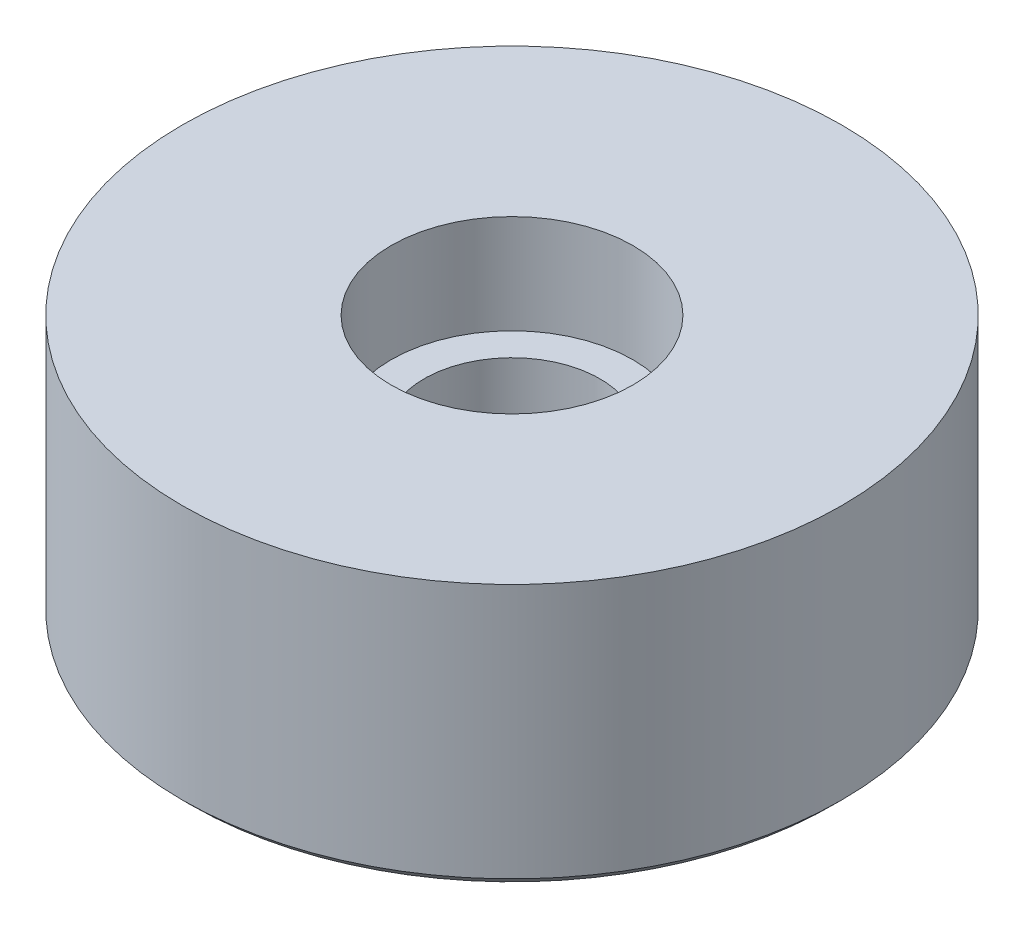
SolidWorks part; units mm, degrees
ref_plane "Front Plane" through (0, 0, 0) normal (0, 0, 1) x (1, 0, 0)
ref_plane "Top Plane" through (0, 0, 0) normal (0, 1, 0) x (1, 0, 0)
ref_plane "Right Plane" through (0, 0, 0) normal (1, 0, 0) x (0, 0, -1)
sketch "Sketch1" plane through (0, 0, 0) normal (0, 1, 0) x (1, 0, 0)
  circle A0 centre (0, 0) radius 15
  circle A1 centre (0, 0) radius 4
  dimension "D1" = 30
  dimension "D2" = 8
extrude "Boss-Extrude1" add sketch "Sketch1" along normal blind 12
ref_plane "Plane1" through (0, 12, 0) normal (0, 1, 0) x (1, 0, 0)
sketch "Sketch2" plane through (0, 12, 0) normal (0, 1, 0) x (1, 0, 0)
  circle A0 centre (0, 0) radius 5.5
  dimension "D1" = 11
extrude "Cut-Extrude1" cut sketch "Sketch2" against normal mid plane 9
chamfer "Chamfer1" distance 0.4 angle 45 1 edges at (0, 0, 15)
